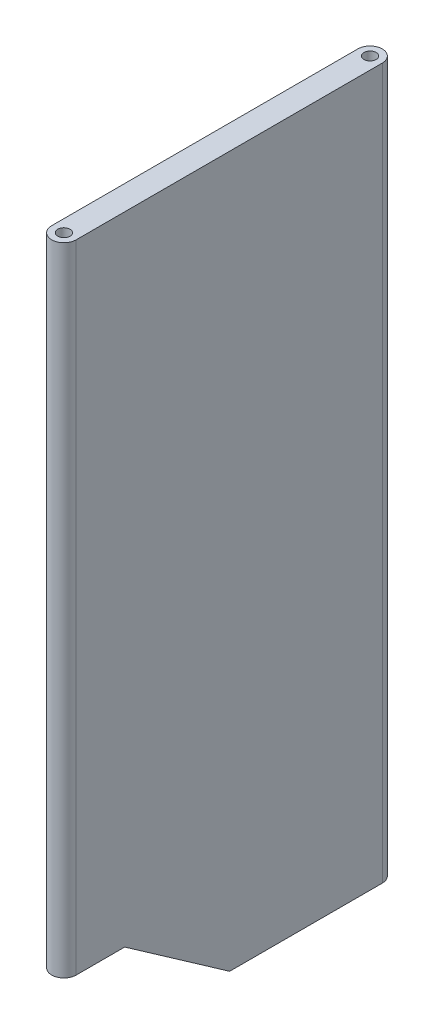
SolidWorks part; units mm, degrees
ref_plane "Спереди" through (0, 0, 0) normal (0, 0, 1) x (1, 0, 0)
ref_plane "Сверху" through (0, 0, 0) normal (0, 1, 0) x (1, 0, 0)
ref_plane "Справа" through (0, 0, 0) normal (1, 0, 0) x (0, 0, -1)
sketch "Эскиз1" plane through (0, 0, 0) normal (1, 0, 0) x (0, 0, -1)
  line L0 (-23, 6) -> (-20.035, 6)
  line L1 (-11.4661, 0) -> (0, 0)
  line L2 (0, 0) -> (0, 58)
  line L3 (0, 58) -> (-23, 58)
  line L4 (-23, 58) -> (-23, 6)
  line L5 (50, 0) -> (-50, 0) construction
  line L6 (0, 50) -> (0, -50) construction
  line L8 (-11.4661, 0) -> (-20.035, 6)
  point P5 (-11.5, 58)
  point P6 (-5.733, 0)
  dimension "D1" = 52
  dimension "D2" = 90
  dimension "D3" = 23
  dimension "D4" = 58
  dimension "D5" = 90
  dimension "D6" = 145
extrude "Бобышка-Вытянуть1" add sketch "Эскиз1" along normal blind 2
sketch "Эскиз2" plane through (0, 0, 0) normal (0, 1, 0) x (1, 0, 0)
  line L0 (-50, 0) -> (50, 0) construction
  line L1 (0, 1) -> (0, 0)
  line L2 (0, 0) -> (2, 0)
  line L3 (2, 0) -> (2, 1)
  circle A0 centre (1, 1) radius 0.5
  arc A1 (0, 1) -> (2, 1) centre (1, 1) cw
  dimension "D1" = 1
  dimension "D2" = 1
extrude "Бобышка-Вытянуть2" add sketch "Эскиз2" along normal blind 58
sketch "Эскиз3" plane through (0, 6, 0) normal (0, -1, 0) x (1, 0, 0)
  line L0 (2, 23) -> (0, 23) construction
  line L1 (0, 23) -> (0, 24)
  line L2 (0, 23) -> (2, 23)
  line L3 (2, 23) -> (2, 20.035) construction
  line L4 (2, 23) -> (2, 24)
  circle A0 centre (1, 24) radius 0.5
  arc A1 (0, 24) -> (2, 24) centre (1, 24) cw
  dimension "D1" = 1
  dimension "D2" = 1
extrude "Бобышка-Вытянуть3" add sketch "Эскиз3" against normal blind 52
